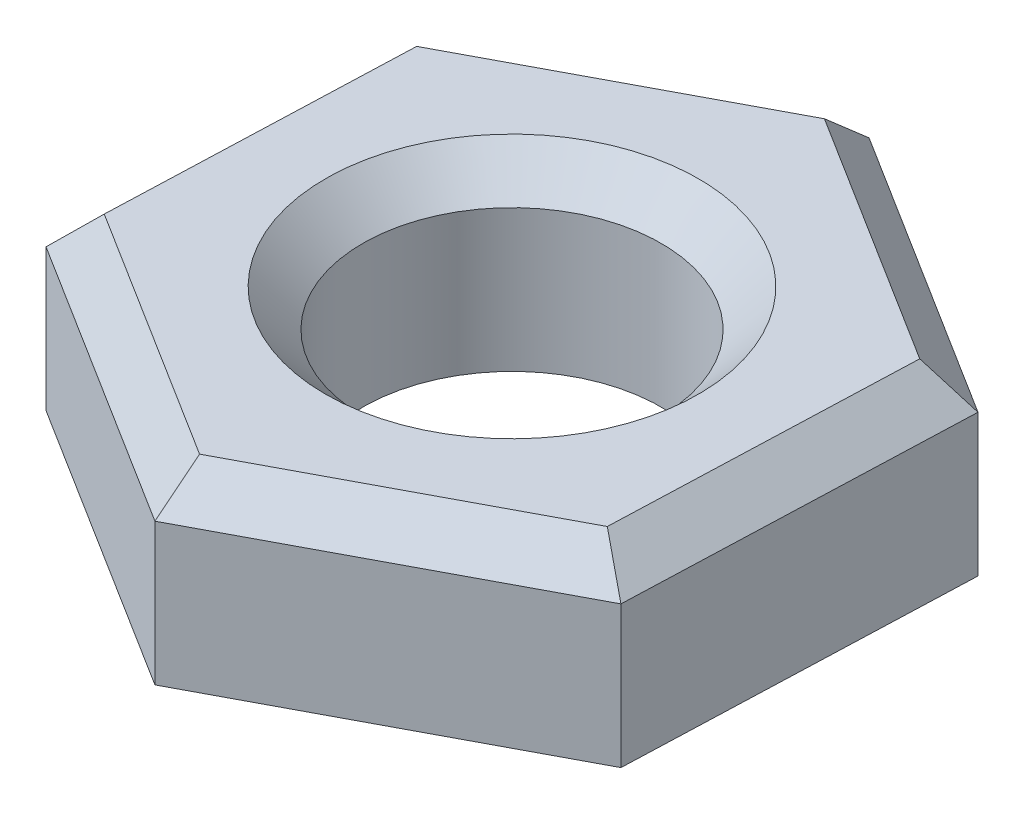
SolidWorks part; units mm, degrees
ref_plane "Front Plane" through (0, 0, 0) normal (0, 0, 1) x (1, 0, 0)
ref_plane "Top Plane" through (0, 0, 0) normal (0, 1, 0) x (1, 0, 0)
ref_plane "Right Plane" through (0, 0, 0) normal (1, 0, 0) x (0, 0, -1)
sketch "Sketch1" plane through (0, 0, 0) normal (0, 1, 0) x (1, 0, 0)
  line L1 (-1.9566, 1.2269) -> (-2.0408, -1.081)
  line L2 (-2.0408, -1.081) -> (-0.0842, -2.3079)
  line L3 (-0.0842, -2.3079) -> (1.9566, -1.2269)
  line L4 (1.9566, -1.2269) -> (2.0408, 1.081)
  line L5 (2.0408, 1.081) -> (0.0842, 2.3079)
  line L6 (0.0842, 2.3079) -> (-1.9566, 1.2269)
  circle A0 centre (0, 0) radius 2 construction
  dimension "D1" = 4
extrude "Boss-Extrude1" add sketch "Sketch1" along normal blind 1.2
sketch "Sketch2" plane through (0, 1.2, 0) normal (0, 1, 0) x (1, 0, 0)
  circle A0 centre (0, 0) radius 1
  dimension "D1" = 2
extrude "Cut-Extrude1" cut sketch "Sketch2" against normal blind 1.6
chamfer "Chamfer1" distance 0.25 angle 45 7 edges at (1.0625, 1.2, -1.6944) (1.9987, 1.2, 0.0729) (0.9362, 1.2, 1.7674) (-1.0625, 1.2, 1.6944) (-1.9987, 1.2, -0.0729) (-0.9362, 1.2, -1.7674) (0, 1.2, 1)
